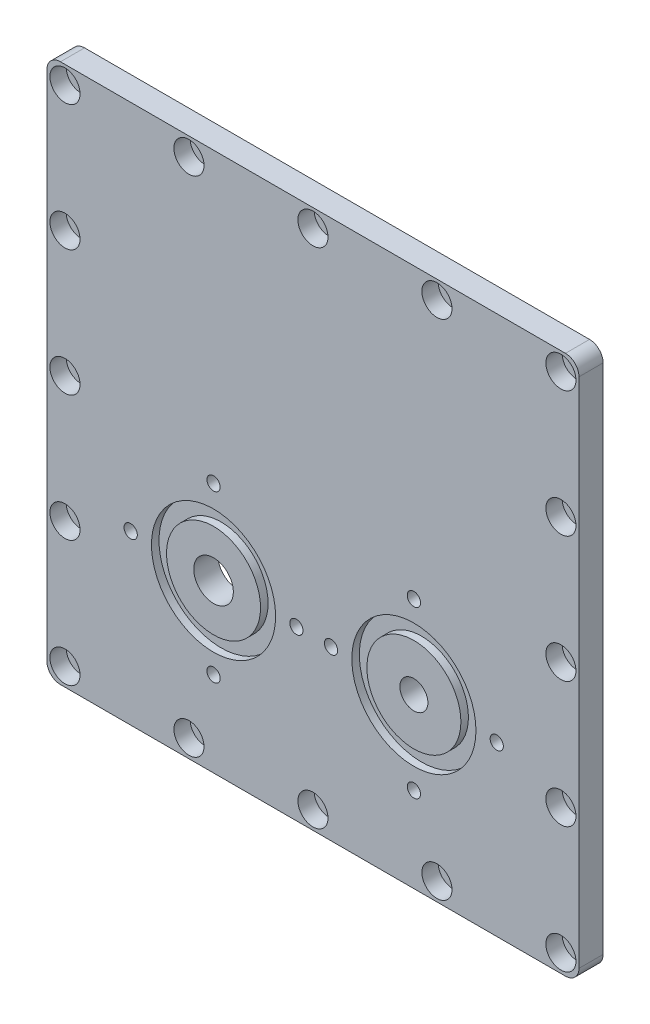
SolidWorks part; units mm, degrees
ref_plane "Front Plane" through (0, 0, 0) normal (0, 0, 1) x (1, 0, 0)
ref_plane "Top Plane" through (0, 0, 0) normal (0, 1, 0) x (1, 0, 0)
ref_plane "Right Plane" through (0, 0, 0) normal (1, 0, 0) x (0, 0, -1)
sketch "Sketch1" plane through (0, 0, 0) normal (0, 0, 1) x (1, 0, 0)
  line L24 (-83.7906, -89.5) -> (83.7906, -89.5)
  line L25 (-88.2906, 85) -> (-88.2906, -85)
  line L26 (83.7906, 89.5) -> (-83.7906, 89.5)
  line L27 (88.2906, -85) -> (88.2906, 85)
  line L28 (-83.7906, -89.5) -> (83.7906, -89.5)
  line L29 (-88.2906, 85) -> (-88.2906, -85)
  line L30 (83.7906, 89.5) -> (-83.7906, 89.5)
  line L31 (88.2906, -85) -> (88.2906, 85)
  arc A21 (83.7906, -89.5) -> (88.2906, -85) centre (83.7906, -85) ccw
  arc A22 (-88.2906, -85) -> (-83.7906, -89.5) centre (-83.7906, -85) ccw
  arc A23 (-83.7906, 89.5) -> (-88.2906, 85) centre (-83.7906, 85) ccw
  arc A24 (88.2906, 85) -> (83.7906, 89.5) centre (83.7906, 85) ccw
  arc A25 (83.7906, -89.5) -> (88.2906, -85) centre (83.7906, -85) ccw
  arc A26 (-88.2906, -85) -> (-83.7906, -89.5) centre (-83.7906, -85) ccw
  arc A27 (-83.7906, 89.5) -> (-88.2906, 85) centre (-83.7906, 85) ccw
  arc A28 (88.2906, 85) -> (83.7906, 89.5) centre (83.7906, 85) ccw
  dimension "D1" = 0.5
extrude "Boss-Extrude1" add sketch "Sketch1" along normal up to surface (8 mm away)
sketch "Sketch2" plane through (0, 0, 8) normal (0, 0, 1) x (1, 0, 0)
  line L0 (-74.25, -98) -> (-69.25, -98) construction
  line L1 (-74.25, -98) -> (-69.25, -98) construction
  line L2 (2.1, 83.5) -> (0, 83.5)
  line L3 (0, 83.5) -> (-2.1, 83.5)
  line L4 (2.1, 83.5) -> (0, 83.5) construction
  line L5 (0, 83.5) -> (-2.1, 83.5) construction
  line L7 (-74.25, -98.5) -> (-69.25, -98.5)
  line L8 (2.5515, 84) -> (0, 84)
  line L9 (0, 84) -> (-2.5515, 84)
  arc A0 (43.2453, 83.5) -> (39.0453, 83.5) centre (41.1453, 83.5) ccw construction
  arc A1 (39.0453, 83.5) -> (43.2453, 83.5) centre (41.1453, 83.5) ccw construction
  arc A2 (43.2453, 83.5) -> (39.0453, 83.5) centre (41.1453, 83.5) ccw construction
  arc A3 (39.0453, 83.5) -> (43.2453, 83.5) centre (41.1453, 83.5) ccw construction
  arc A4 (2.1, 83.5) -> (-2.1, 83.5) centre (0, 83.5) ccw construction
  arc A5 (-2.1, 83.5) -> (2.1, 83.5) centre (0, 83.5) ccw
  arc A6 (-2.1, 83.5) -> (2.1, 83.5) centre (0, 83.5) ccw construction
  arc A7 (2.1, 83.5) -> (-2.1, 83.5) centre (0, 83.5) ccw construction
  arc A8 (-84.3906, -41.75) -> (-80.1906, -41.75) centre (-82.2906, -41.75) ccw construction
  arc A9 (-80.1906, -41.75) -> (-84.3906, -41.75) centre (-82.2906, -41.75) ccw construction
  arc A10 (-84.3906, 0) -> (-80.1906, 0) centre (-82.2906, 0) ccw construction
  arc A11 (-80.1906, 0) -> (-84.3906, 0) centre (-82.2906, 0) ccw construction
  arc A12 (-43.2453, 83.5) -> (-39.0453, 83.5) centre (-41.1453, 83.5) ccw construction
  arc A13 (-84.3906, 83.5) -> (-80.1906, 83.5) centre (-82.2906, 83.5) ccw construction
  arc A14 (-84.3906, 41.75) -> (-80.1906, 41.75) centre (-82.2906, 41.75) ccw construction
  arc A15 (-80.1906, 41.75) -> (-84.3906, 41.75) centre (-82.2906, 41.75) ccw construction
  arc A16 (-80.1906, 83.5) -> (-84.3906, 83.5) centre (-82.2906, 83.5) ccw construction
  arc A17 (-39.0453, 83.5) -> (-43.2453, 83.5) centre (-41.1453, 83.5) ccw construction
  arc A18 (-84.3906, -41.75) -> (-80.1906, -41.75) centre (-82.2906, -41.75) ccw construction
  arc A19 (-80.1906, -41.75) -> (-84.3906, -41.75) centre (-82.2906, -41.75) ccw construction
  arc A20 (-84.3906, 0) -> (-80.1906, 0) centre (-82.2906, 0) ccw construction
  arc A21 (-80.1906, 0) -> (-84.3906, 0) centre (-82.2906, 0) ccw construction
  arc A22 (-43.2453, 83.5) -> (-39.0453, 83.5) centre (-41.1453, 83.5) ccw construction
  arc A23 (-84.3906, 83.5) -> (-80.1906, 83.5) centre (-82.2906, 83.5) ccw construction
  arc A24 (-84.3906, 41.75) -> (-80.1906, 41.75) centre (-82.2906, 41.75) ccw construction
  arc A25 (-80.1906, 41.75) -> (-84.3906, 41.75) centre (-82.2906, 41.75) ccw construction
  arc A26 (-80.1906, 83.5) -> (-84.3906, 83.5) centre (-82.2906, 83.5) ccw construction
  arc A27 (-39.0453, 83.5) -> (-43.2453, 83.5) centre (-41.1453, 83.5) ccw construction
  arc A28 (80.1906, -41.75) -> (84.3906, -41.75) centre (82.2906, -41.75) ccw construction
  arc A29 (84.3906, -41.75) -> (80.1906, -41.75) centre (82.2906, -41.75) ccw construction
  arc A30 (80.1906, -83.5) -> (84.3906, -83.5) centre (82.2906, -83.5) ccw construction
  arc A31 (84.3906, -83.5) -> (80.1906, -83.5) centre (82.2906, -83.5) ccw construction
  arc A32 (39.0453, -83.5) -> (43.2453, -83.5) centre (41.1453, -83.5) ccw construction
  arc A33 (43.2453, -83.5) -> (39.0453, -83.5) centre (41.1453, -83.5) ccw construction
  arc A34 (-2.1, -83.5) -> (2.1, -83.5) centre (0, -83.5) ccw construction
  arc A35 (2.1, -83.5) -> (-2.1, -83.5) centre (0, -83.5) ccw construction
  arc A36 (-43.2453, -83.5) -> (-39.0453, -83.5) centre (-41.1453, -83.5) ccw construction
  arc A37 (-39.0453, -83.5) -> (-43.2453, -83.5) centre (-41.1453, -83.5) ccw construction
  arc A38 (-80.1906, -83.5) -> (-84.3906, -83.5) centre (-82.2906, -83.5) ccw construction
  arc A39 (-84.3906, -83.5) -> (-80.1906, -83.5) centre (-82.2906, -83.5) ccw construction
  arc A40 (80.1906, -41.75) -> (84.3906, -41.75) centre (82.2906, -41.75) ccw construction
  arc A41 (84.3906, -41.75) -> (80.1906, -41.75) centre (82.2906, -41.75) ccw construction
  arc A42 (80.1906, -83.5) -> (84.3906, -83.5) centre (82.2906, -83.5) ccw construction
  arc A43 (84.3906, -83.5) -> (80.1906, -83.5) centre (82.2906, -83.5) ccw construction
  arc A44 (39.0453, -83.5) -> (43.2453, -83.5) centre (41.1453, -83.5) ccw construction
  arc A45 (43.2453, -83.5) -> (39.0453, -83.5) centre (41.1453, -83.5) ccw construction
  arc A46 (-2.1, -83.5) -> (2.1, -83.5) centre (0, -83.5) ccw construction
  arc A47 (2.1, -83.5) -> (-2.1, -83.5) centre (0, -83.5) ccw construction
  arc A48 (-43.2453, -83.5) -> (-39.0453, -83.5) centre (-41.1453, -83.5) ccw construction
  arc A49 (-39.0453, -83.5) -> (-43.2453, -83.5) centre (-41.1453, -83.5) ccw construction
  arc A50 (-80.1906, -83.5) -> (-84.3906, -83.5) centre (-82.2906, -83.5) ccw construction
  arc A51 (-84.3906, -83.5) -> (-80.1906, -83.5) centre (-82.2906, -83.5) ccw construction
  arc A52 (80.1906, 83.5) -> (84.3906, 83.5) centre (82.2906, 83.5) ccw construction
  arc A53 (84.3906, 83.5) -> (80.1906, 83.5) centre (82.2906, 83.5) ccw construction
  arc A54 (80.1906, 41.75) -> (84.3906, 41.75) centre (82.2906, 41.75) ccw construction
  arc A55 (84.3906, 41.75) -> (80.1906, 41.75) centre (82.2906, 41.75) ccw construction
  arc A56 (80.1906, 0) -> (84.3906, 0) centre (82.2906, 0) ccw construction
  arc A57 (84.3906, 0) -> (80.1906, 0) centre (82.2906, 0) ccw construction
  arc A58 (80.1906, 83.5) -> (84.3906, 83.5) centre (82.2906, 83.5) ccw construction
  arc A59 (84.3906, 83.5) -> (80.1906, 83.5) centre (82.2906, 83.5) ccw construction
  arc A60 (80.1906, 41.75) -> (84.3906, 41.75) centre (82.2906, 41.75) ccw construction
  arc A61 (84.3906, 41.75) -> (80.1906, 41.75) centre (82.2906, 41.75) ccw construction
  arc A62 (80.1906, 0) -> (84.3906, 0) centre (82.2906, 0) ccw construction
  arc A63 (84.3906, 0) -> (80.1906, 0) centre (82.2906, 0) ccw construction
  arc A64 (-2.5515, 84) -> (2.5515, 84) centre (0, 83.5) ccw
  arc A65 (43.7453, 83.5) -> (38.5453, 83.5) centre (41.1453, 83.5) ccw
  arc A66 (38.5453, 83.5) -> (43.7453, 83.5) centre (41.1453, 83.5) ccw
  arc A67 (2.6, 83.5) -> (-2.6, 83.5) centre (0, 83.5) ccw
  arc A68 (-84.8906, -41.75) -> (-79.6906, -41.75) centre (-82.2906, -41.75) ccw
  arc A69 (-79.6906, -41.75) -> (-84.8906, -41.75) centre (-82.2906, -41.75) ccw
  arc A70 (-84.8906, 0) -> (-79.6906, 0) centre (-82.2906, 0) ccw
  arc A71 (-79.6906, 0) -> (-84.8906, 0) centre (-82.2906, 0) ccw
  arc A72 (-43.7453, 83.5) -> (-38.5453, 83.5) centre (-41.1453, 83.5) ccw
  arc A73 (-38.5453, 83.5) -> (-43.7453, 83.5) centre (-41.1453, 83.5) ccw
  arc A74 (-84.8906, 83.5) -> (-79.6906, 83.5) centre (-82.2906, 83.5) ccw
  arc A75 (-79.6906, 83.5) -> (-84.8906, 83.5) centre (-82.2906, 83.5) ccw
  arc A76 (-84.8906, 41.75) -> (-79.6906, 41.75) centre (-82.2906, 41.75) ccw
  arc A77 (-79.6906, 41.75) -> (-84.8906, 41.75) centre (-82.2906, 41.75) ccw
  arc A78 (79.6906, -41.75) -> (84.8906, -41.75) centre (82.2906, -41.75) ccw
  arc A79 (84.8906, -41.75) -> (79.6906, -41.75) centre (82.2906, -41.75) ccw
  arc A80 (79.6906, -83.5) -> (84.8906, -83.5) centre (82.2906, -83.5) ccw
  arc A81 (84.8906, -83.5) -> (79.6906, -83.5) centre (82.2906, -83.5) ccw
  arc A82 (38.5453, -83.5) -> (43.7453, -83.5) centre (41.1453, -83.5) ccw
  arc A83 (43.7453, -83.5) -> (38.5453, -83.5) centre (41.1453, -83.5) ccw
  arc A84 (-2.6, -83.5) -> (2.6, -83.5) centre (0, -83.5) ccw
  arc A85 (2.6, -83.5) -> (-2.6, -83.5) centre (0, -83.5) ccw
  arc A86 (-43.7453, -83.5) -> (-38.5453, -83.5) centre (-41.1453, -83.5) ccw
  arc A87 (-38.5453, -83.5) -> (-43.7453, -83.5) centre (-41.1453, -83.5) ccw
  arc A88 (-79.6906, -83.5) -> (-84.8906, -83.5) centre (-82.2906, -83.5) ccw
  arc A89 (-84.8906, -83.5) -> (-79.6906, -83.5) centre (-82.2906, -83.5) ccw
  arc A90 (79.6906, 83.5) -> (84.8906, 83.5) centre (82.2906, 83.5) ccw
  arc A91 (84.8906, 83.5) -> (79.6906, 83.5) centre (82.2906, 83.5) ccw
  arc A92 (79.6906, 41.75) -> (84.8906, 41.75) centre (82.2906, 41.75) ccw
  arc A93 (84.8906, 41.75) -> (79.6906, 41.75) centre (82.2906, 41.75) ccw
  arc A94 (79.6906, 0) -> (84.8906, 0) centre (82.2906, 0) ccw
  arc A95 (84.8906, 0) -> (79.6906, 0) centre (82.2906, 0) ccw
  dimension "D1" = 0
  dimension "D2" = 0.5
extrude "Cut-Extrude1" cut sketch "Sketch2" against normal blind 90 contours A65 A66 | L8 A67 L9 | L9 A64 L8 | A72 A73 | A74 A75 | A76 A77 | A70 A71 | A88 A89 | A68 A69 | A86 A87 | A84 A85 | A82 A83 | A80 A81 | A78 A79 | A94 A95 | A92 A93 | A90 A91
sketch "Sketch3" plane through (0, 0, 8) normal (0, 0, 1) x (1, 0, 0)
  circle A0 centre (41.1453, 83.5) radius 5
  circle A1 centre (41.1453, 83.5) radius 2.6
  circle A2 centre (41.1453, 83.5) radius 2.6 construction
  circle A3 centre (82.2906, 83.5) radius 2.6
  circle A4 centre (82.2906, 83.5) radius 2.6 construction
  circle A5 centre (82.2906, 41.75) radius 2.6
  circle A6 centre (82.2906, 41.75) radius 2.6 construction
  circle A7 centre (82.2906, 0) radius 2.6
  circle A8 centre (82.2906, 0) radius 2.6 construction
  circle A9 centre (82.2906, -41.75) radius 2.6
  circle A10 centre (82.2906, -41.75) radius 2.6 construction
  circle A11 centre (82.2906, -83.5) radius 2.6
  circle A12 centre (82.2906, -83.5) radius 2.6 construction
  circle A13 centre (41.1453, -83.5) radius 2.6
  circle A14 centre (41.1453, -83.5) radius 2.6 construction
  circle A15 centre (0, -83.5) radius 2.6
  circle A16 centre (0, -83.5) radius 2.6 construction
  circle A17 centre (-82.2906, 0) radius 2.6
  circle A18 centre (-82.2906, 0) radius 2.6 construction
  circle A19 centre (-82.2906, -83.5) radius 2.6
  circle A20 centre (-82.2906, -83.5) radius 2.6 construction
  circle A21 centre (-82.2906, -41.75) radius 2.6
  circle A22 centre (-82.2906, -41.75) radius 2.6 construction
  circle A23 centre (-41.1453, -83.5) radius 2.6
  circle A24 centre (-41.1453, -83.5) radius 2.6 construction
  circle A25 centre (-82.2906, 41.75) radius 2.6
  circle A26 centre (-82.2906, 41.75) radius 2.6 construction
  circle A27 centre (-82.2906, 83.5) radius 2.6
  circle A28 centre (-82.2906, 83.5) radius 2.6 construction
  circle A29 centre (-41.1453, 83.5) radius 2.6
  circle A30 centre (-41.1453, 83.5) radius 2.6 construction
  circle A31 centre (0, 83.5) radius 2.6
  circle A32 centre (0, 83.5) radius 2.6 construction
  circle A33 centre (82.2906, 83.5) radius 5
  circle A34 centre (82.2906, 41.75) radius 5
  circle A35 centre (82.2906, 0) radius 5
  circle A36 centre (82.2906, -41.75) radius 5
  circle A37 centre (82.2906, -83.5) radius 5
  circle A38 centre (41.1453, -83.5) radius 5
  circle A39 centre (0, -83.5) radius 5
  circle A40 centre (-82.2906, 0) radius 5
  circle A41 centre (-82.2906, -83.5) radius 5
  circle A42 centre (-82.2906, -41.75) radius 5
  circle A43 centre (-41.1453, -83.5) radius 5
  circle A44 centre (-82.2906, 41.75) radius 5
  circle A45 centre (-82.2906, 83.5) radius 5
  circle A46 centre (-41.1453, 83.5) radius 5
  circle A47 centre (0, 83.5) radius 5
  dimension "D1" = 0
  dimension "D2" = 0
  dimension "D3" = 0
  dimension "D4" = 0
  dimension "D5" = 0
  dimension "D6" = 0
  dimension "D7" = 0
  dimension "D8" = 0
  dimension "D9" = 0
  dimension "D10" = 0
  dimension "D11" = 0
  dimension "D12" = 0
  dimension "D13" = 0
  dimension "D14" = 0
  dimension "D15" = 0
  dimension "D16" = 0
  dimension "D17" = 2.4
extrude "Cut-Extrude2" cut sketch "Sketch3" against normal blind 5.4
sketch "Sketch5" plane through (0, 0, 8) normal (0, 0, 1) x (1, 0, 0)
  circle A2 centre (33.4966, -6.2548) radius 2.2
  circle A4 centre (5.9966, -33.7548) radius 2.2
  circle A6 centre (33.4966, -61.2548) radius 2.2
  circle A8 centre (60.9966, -33.7548) radius 2.2
  circle A10 centre (33.4966, -33.7548) radius 4.65
extrude "Cut-Extrude3" cut sketch "Sketch5" against normal blind 20
sketch "Sketch6" plane through (0, 0, 8) normal (0, 0, 1) x (1, 0, 0)
  circle A2 centre (33.4966, -33.7548) radius 20.6
  circle A3 centre (33.4966, -33.7548) radius 15.6
extrude "Cut-Extrude4" cut sketch "Sketch6" against normal blind 2.5
sketch "Sketch7" plane through (0, 0, 8) normal (0, 0, 1) x (1, 0, 0)
  circle A4 centre (-32.9906, -34.2) radius 15.6
  circle A5 centre (-32.9906, -34.2) radius 20.6
extrude "Cut-Extrude5" cut sketch "Sketch7" against normal blind 2.5
sketch "Sketch9" plane through (0, 0, 8) normal (0, 0, 1) x (1, 0, 0)
  circle A0 centre (-32.9906, -34.2) radius 6.575 construction
  circle A1 centre (-32.9906, -34.2) radius 6.575
  circle A3 centre (-32.9906, -23.0748) radius 1.025
  circle A4 centre (-32.9906, -23.0748) radius 1.025
  circle A5 centre (-32.9906, -45.3252) radius 1.025
  circle A6 centre (-32.9906, -45.3252) radius 1.025
  circle A7 centre (-32.9906, -34.2) radius 8.875
  circle A8 centre (-32.9906, -34.2) radius 8.875
  circle A9 centre (-5.4906, -33.7548) radius 2.2
  circle A10 centre (-5.4906, -33.7548) radius 2.2
  circle A11 centre (-32.9906, -61.2548) radius 2.2
  circle A12 centre (-32.9906, -61.2548) radius 2.2
  circle A13 centre (-60.4906, -33.7548) radius 2.2
  circle A14 centre (-60.4906, -33.7548) radius 2.2
  circle A15 centre (-32.9906, -6.2548) radius 2.2
  circle A16 centre (-32.9906, -6.2548) radius 2.2
  dimension "D1" = 0
  dimension "D2" = 0
  dimension "D3" = 0
  dimension "D4" = 0
  dimension "D5" = 0
  dimension "D6" = 0
  dimension "D7" = 0
extrude "Cut-Extrude6" cut sketch "Sketch9" against normal up to next contours A10 | A16 | A12 | A1 | A14
